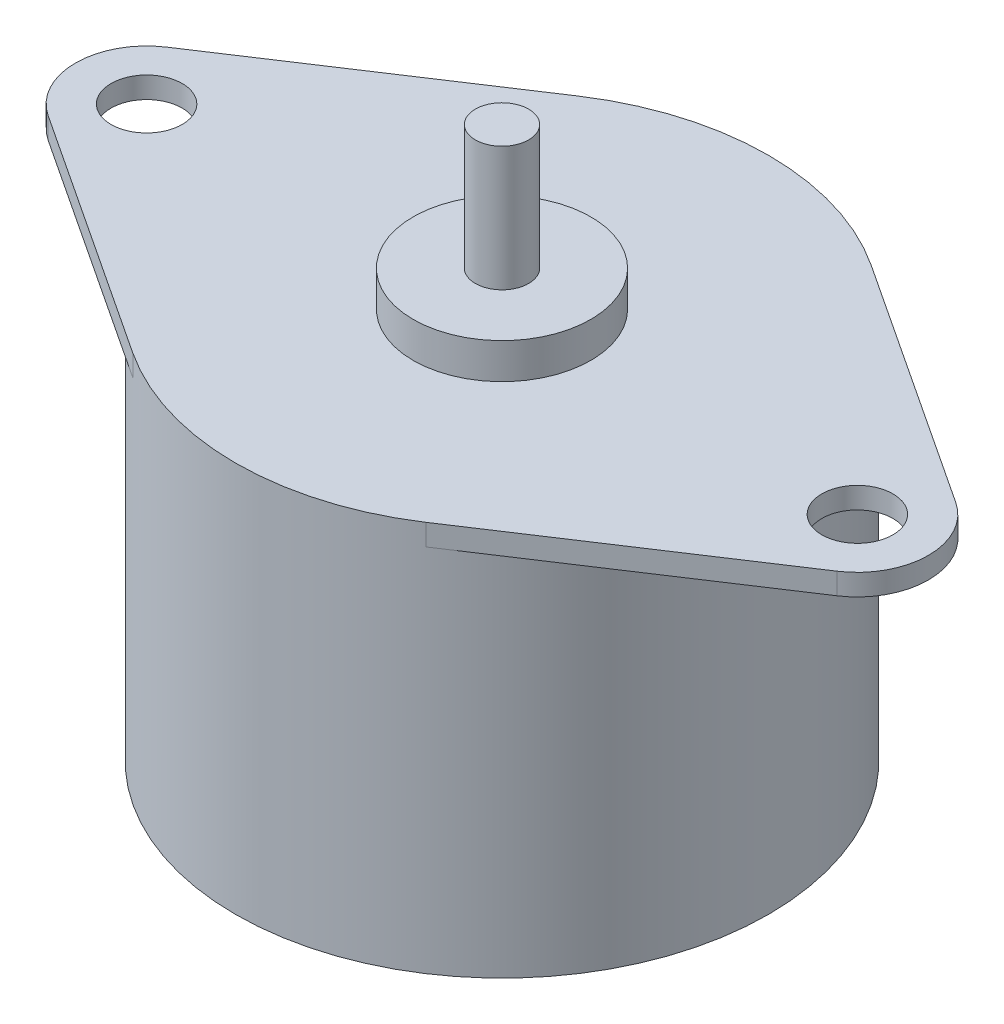
SolidWorks part; units mm, degrees
ref_plane "Front Plane" through (0, 0, 0) normal (0, 0, 1) x (1, 0, 0)
ref_plane "Top Plane" through (0, 0, 0) normal (0, 1, 0) x (1, 0, 0)
ref_plane "Right Plane" through (0, 0, 0) normal (1, 0, 0) x (0, 0, -1)
sketch "Sketch1" plane through (0, 0, 0) normal (0, 1, 0) x (1, 0, 0)
  circle A0 centre (0, 0) radius 7.5
  dimension "D1" = 15
extrude "Boss-Extrude1" add sketch "Sketch1" along normal blind 10.4
sketch "Sketch2" plane through (0, 0, 0) normal (0, -1, 0) x (1, 0, 0)
  circle A0 centre (0, 0) radius 3
  dimension "D1" = 6
extrude "Boss-Extrude2" add sketch "Sketch2" along normal blind 1
sketch "Sketch3" plane through (0, 10.4, 0) normal (0, 1, 0) x (1, 0, 0)
  line L0 (-11.1, 1.6703) -> (-4.125, 6.2637)
  line L1 (4.125, 6.2637) -> (11.1, 1.6703)
  line L2 (11.1, -1.6703) -> (4.125, -6.2637)
  line L3 (-11.1, -1.6703) -> (-4.125, -6.2637)
  circle A0 centre (0, 0) radius 7.5 construction
  arc A1 (-11.1, 1.6703) -> (-11.1, -1.6703) centre (-10, 0) ccw
  arc A2 (-4.125, 6.2637) -> (4.125, 6.2637) centre (0, 0) cw
  arc A3 (11.1, 1.6703) -> (11.1, -1.6703) centre (10, 0) cw
  arc A4 (4.125, -6.2637) -> (-4.125, -6.2637) centre (0, 0) cw
  circle A5 centre (-10, 0) radius 1
  circle A6 centre (10, 0) radius 1
  dimension "D2" = 2
  dimension "D3" = 2
  dimension "D1" = 20
extrude "Boss-Extrude3" add sketch "Sketch3" along normal blind 0.6
sketch "Sketch4" plane through (0, 11, 0) normal (0, 1, 0) x (1, 0, 0)
  circle A0 centre (0, 0) radius 2.5
  dimension "D1" = 5
extrude "Boss-Extrude4" add sketch "Sketch4" along normal blind 1
sketch "Sketch5" plane through (0, 12, 0) normal (0, 1, 0) x (1, 0, 0)
  circle A0 centre (0, 0) radius 0.75
  dimension "D1" = 1.5
extrude "Boss-Extrude5" add sketch "Sketch5" along normal blind 3.5
sketch "Sketch6" plane through (0, -1, 0) normal (0, -1, 0) x (1, 0, 0)
  circle A0 centre (0, 0) radius 0.75
  dimension "D1" = 1.5
extrude "Boss-Extrude6" add sketch "Sketch6" along normal blind 1
